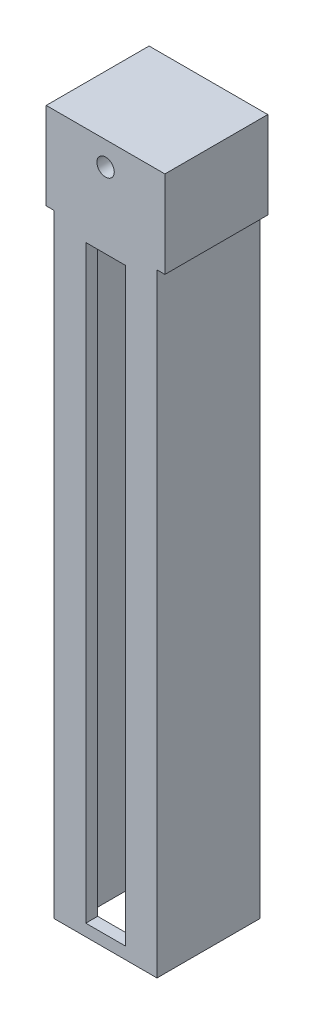
SolidWorks part; units mm, degrees
ref_plane "Front Plane" through (0, 0, 0) normal (0, 0, 1) x (1, 0, 0)
ref_plane "Top Plane" through (0, 0, 0) normal (0, 1, 0) x (1, 0, 0)
ref_plane "Right Plane" through (0, 0, 0) normal (1, 0, 0) x (0, 0, -1)
sketch "Sketch1" plane through (0, 0, 0) normal (0, 1, 0) x (1, 0, 0)
  line L1 (-13, -13) -> (13, -13)
  line L2 (-13, -13) -> (-13, 13)
  line L3 (-13, 13) -> (13, 13)
  line L4 (13, -13) -> (13, 13)
  line L5 (-13, -13) -> (13, 13) construction
  line L6 (-13, 13) -> (13, -13) construction
  point P0 (0, 0)
  dimension "D1" = 26
  dimension "D2" = 26
extrude "Boss-Extrude1" add sketch "Sketch1" along normal blind 155
shell "Shell1" thickness 3
sketch "Sketch2" plane through (0, 0, 13) normal (0, 0, 1) x (1, 0, 0)
  line L1 (5, 3) -> (-5, 3)
  line L2 (5, 3) -> (5, 152)
  line L3 (5, 152) -> (-5, 152)
  line L4 (-5, 3) -> (-5, 152)
  line L5 (5, 3) -> (-5, 152) construction
  line L6 (5, 152) -> (-5, 3) construction
  line L7 (-13, 155) -> (-13, 0) construction
  line L8 (-13, 0) -> (13, 0) construction
  point P0 (0, 77.5)
  dimension "D1" = 13
  dimension "D2" = 10
  dimension "D3" = 3
  dimension "D4" = 152
extrude "Cut-Extrude1" cut sketch "Sketch2" against normal blind 3
sketch "Sketch3" plane through (0, 155, 0) normal (0, 1, 0) x (1, 0, 0)
  line L1 (-15, -13) -> (15, -13)
  line L2 (-15, -13) -> (-15, 13)
  line L3 (-15, 13) -> (15, 13)
  line L4 (15, -13) -> (15, 13)
  line L5 (-15, -13) -> (15, 13) construction
  line L6 (-15, 13) -> (15, -13) construction
  point P0 (0, 0)
  point P5 (0, 0)
  dimension "D1" = 30
  dimension "D2" = 26
  dimension "D3" = 0
  dimension "D4" = 0
extrude "Boss-Extrude2" add sketch "Sketch3" along normal blind 22
sketch "Sketch4" plane through (0, 0, 13) normal (0, 0, 1) x (1, 0, 0)
  line L0 (-15, 177) -> (15, 177) construction
  line L1 (0, 177) -> (0, 0) construction
  circle A0 centre (0, 171) radius 2.2
  dimension "D1" = 4.4
  dimension "D2" = 6
extrude "Cut-Extrude2" cut sketch "Sketch4" against normal through all
